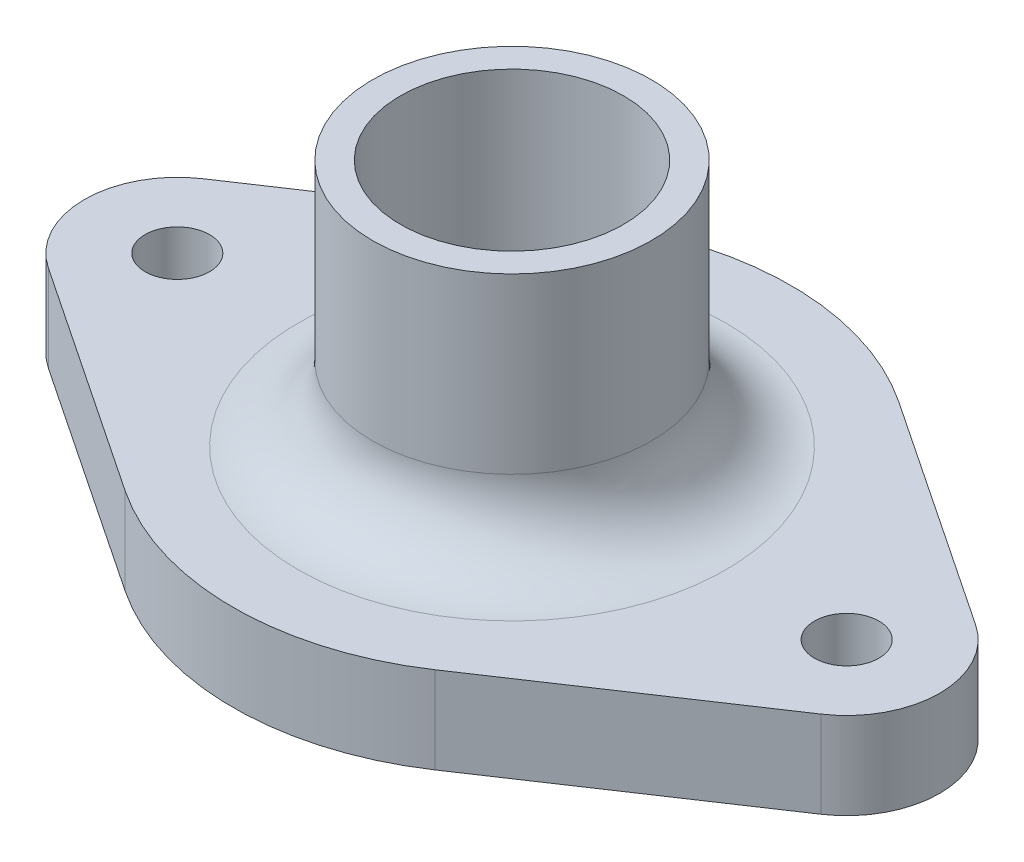
SolidWorks part; units mm, degrees
material "ABS"
ref_plane "Ön Düzlem" through (0, 0, 0) normal (0, 0, 1) x (1, 0, 0)
ref_plane "Üst Düzlem" through (0, 0, 0) normal (0, 1, 0) x (1, 0, 0)
ref_plane "Sağ Düzlem" through (0, 0, 0) normal (1, 0, 0) x (0, 0, -1)
sketch "Çizim1" plane through (0, 0, 0) normal (0, 1, 0) x (1, 0, 0)
  line L1 (-31.1667, 6.2361) -> (-12.5, 18.7083)
  line L2 (-31.1667, -6.2361) -> (-12.5, -18.7083)
  line L3 (12.5, 18.7083) -> (31.1667, 6.2361)
  line L4 (12.5, -18.7083) -> (31.1667, -6.2361)
  arc A0 (12.5, 18.7083) -> (-12.5, 18.7083) centre (0, 0) ccw
  arc A2 (-31.1667, 6.2361) -> (-31.1667, -6.2361) centre (-27, 0) ccw
  arc A3 (31.1667, -6.2361) -> (31.1667, 6.2361) centre (27, 0) ccw
  circle A4 centre (-27, 0) radius 2.6
  arc A5 (-12.5, -18.7083) -> (12.5, -18.7083) centre (0, 0) ccw
  circle A6 centre (27, 0) radius 2.6
  point P6 (0, 0)
  dimension "D1" = 22.5
  dimension "D2" = 7.5
  dimension "D4" = 5.2
  dimension "D5" = 5.2
  dimension "D3" = 54
extrude "Yükseklik-Ekstrüzyon1" add sketch "Çizim1" along normal blind 7
sketch "Çizim3" plane through (0, 7, 0) normal (0, 1, 0) x (1, 0, 0)
  circle A0 centre (0, 0) radius 11.25
  circle A1 centre (0, 0) radius 8
  dimension "D1" = 22.5
  dimension "D2" = 16
extrude "Yükseklik-Ekstrüzyon2" add sketch "Çizim3" along normal blind 20
sketch "Çizim4" plane through (0, 7, 0) normal (0, 1, 0) x (1, 0, 0)
  circle A0 centre (0, 0) radius 9
  dimension "D1" = 18
extrude "Kes-Ekstrüzyon1" cut sketch "Çizim4" against normal blind 5 and the other way blind 40
fillet "Radyus2" radius 6 1 edges at (0, 7, 11.25)
